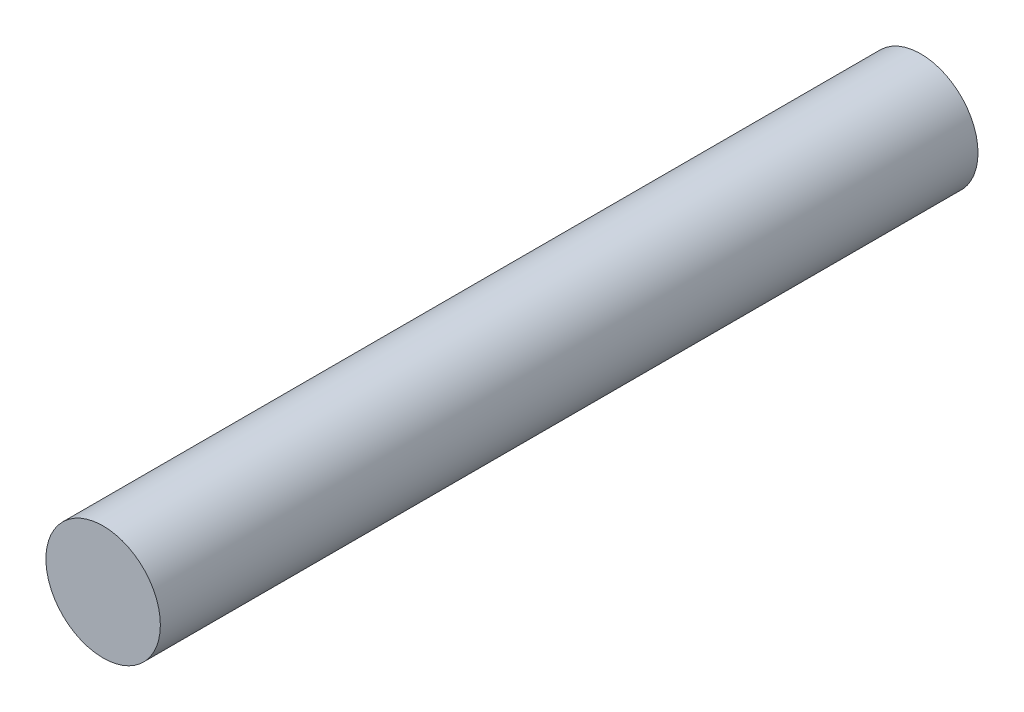
SolidWorks part; units mm, degrees
ref_plane "Front Plane" through (0, 0, 0) normal (0, 0, 1) x (1, 0, 0)
ref_plane "Top Plane" through (0, 0, 0) normal (0, 1, 0) x (1, 0, 0)
ref_plane "Right Plane" through (0, 0, 0) normal (1, 0, 0) x (0, 0, -1)
sketch "Sketch1" plane through (0, 0, 0) normal (0, 0, 1) x (1, 0, 0)
  circle A0 centre (0, 0) radius 2.8
  dimension "D1" = 5.6
extrude "Boss-Extrude1" add sketch "Sketch1" along normal blind 40
